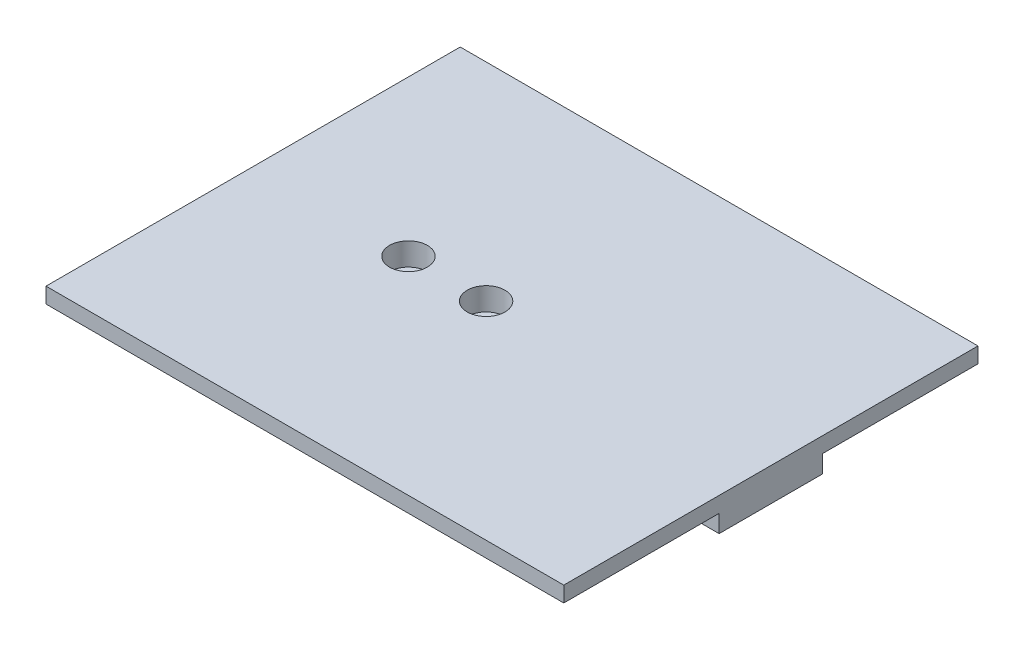
SolidWorks part; units mm, degrees
ref_plane "前基準面" through (0, 0, 0) normal (0, 0, 1) x (1, 0, 0)
ref_plane "上基準面" through (0, 0, 0) normal (0, 1, 0) x (1, 0, 0)
ref_plane "右基準面" through (0, 0, 0) normal (1, 0, 0) x (0, 0, -1)
sketch "草圖1" plane through (0, 0, 0) normal (0, 1, 0) x (1, 0, 0)
  line L0 (0, 0) -> (-50, 0) construction
  line L1 (50, -40) -> (-50, -40)
  line L2 (50, -40) -> (50, 40)
  line L3 (50, 40) -> (-50, 40)
  line L4 (-50, -40) -> (-50, 40)
  line L5 (50, -40) -> (-50, 40) construction
  line L6 (50, 40) -> (-50, -40) construction
  point P0 (0, 0)
  dimension "D1" = 80
  dimension "D2" = 100
extrude "填料-伸長1" add sketch "草圖1" along normal blind 3
sketch "草圖2" plane through (0, 0, 0) normal (0, -1, 0) x (1, 0, 0)
  line L0 (-50, -40) -> (-50, 40) construction
  line L1 (50, -10) -> (-50, -10)
  line L2 (50, -10) -> (50, 10)
  line L3 (50, 10) -> (-50, 10)
  line L4 (-50, -10) -> (-50, 10)
  line L5 (50, -10) -> (-50, 10) construction
  line L6 (50, 10) -> (-50, -10) construction
  point P0 (0, 0)
  dimension "D1" = 20
extrude "填料-伸長2" add sketch "草圖2" along normal blind 3.4
sketch "草圖3" plane through (0, 3, 0) normal (0, 1, 0) x (1, 0, 0)
  line L0 (0, 0) -> (-50, 0) construction
  line L1 (-50, 40) -> (-50, -40) construction
  circle A0 centre (-20, 0) radius 3.15
  circle A1 centre (-5, 0) radius 3.15
  dimension "D1" = 6.3
  dimension "D2" = 15
  dimension "D3" = 30
hole_wizard "M4 六角承窩頭蓋螺釘的柱孔1" positions "草圖5" profile "草圖7" counterbore size "M4" standard "ISO" end condition through all
sketch "草圖5" plane through (0, 3, 0) normal (0, 1, 0) x (1, 0, 0)
  point P0 (-20, 0)
  point P3 (-5, 0)
sketch "草圖7" plane through (-20, 3, 0) normal (1, 0, 0) x (0, 0, 1)
  line L0 (0, 0) -> (0, 6.4)
  line L1 (0, 6.4) -> (2.1, 6.4)
  line L3 (2.1, 6.4) -> (2.1, 4.4)
  line L4 (2.1, 4.4) -> (3.65, 4.4)
  line L5 (3.65, 4.4) -> (3.65, 0)
  line L7 (3.65, 0) -> (0, 0)
  line L11 (0, -6.35) -> (0, 107.95) construction
  dimension "貫穿孔直徑" = 4.2
  dimension "貫穿孔深度" = 6.4
  dimension "柱孔直徑" = 7.3
  dimension "柱孔深度" = 4.4
